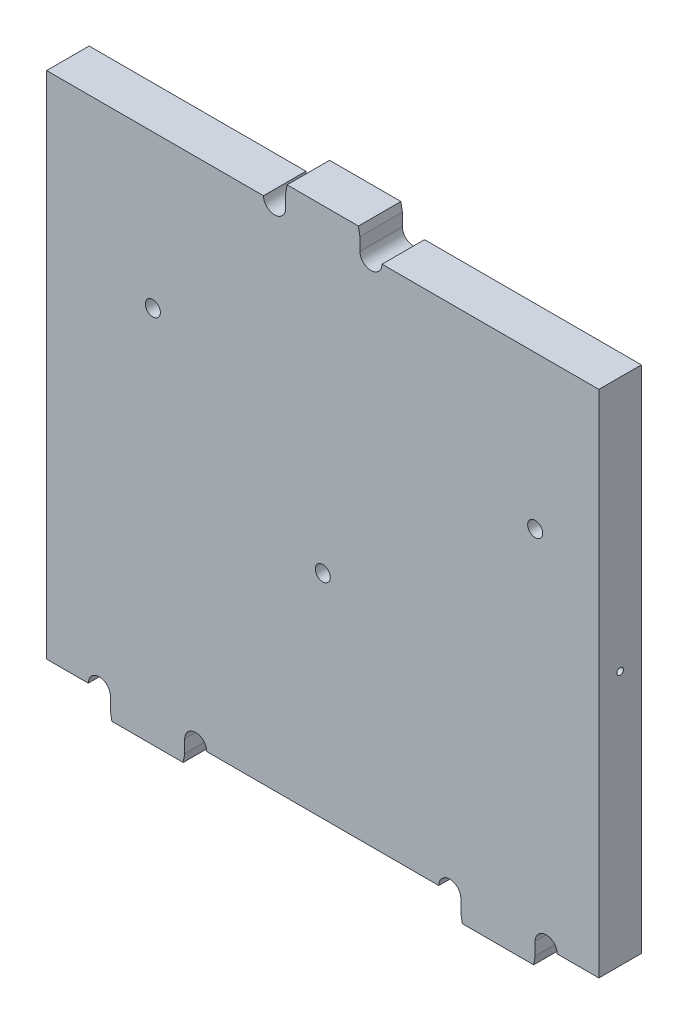
SolidWorks part; units mm, degrees
material "Delrin 2700 NC010, Low Viscosity Acetal Copolymer (SS)"
ref_plane "Front Plane" through (0, 0, 0) normal (0, 0, 1) x (1, 0, 0)
ref_plane "Top Plane" through (0, 0, 0) normal (0, 1, 0) x (1, 0, 0)
ref_plane "Right Plane" through (0, 0, 0) normal (1, 0, 0) x (0, 0, -1)
sketch "Sketch1" plane through (0, 0, 0) normal (0, 0, 1) x (1, 0, 0)
  line L1 (-82.55, -76.2) -> (82.55, -76.2)
  line L2 (-82.55, -76.2) -> (-82.55, 76.2)
  line L3 (-82.55, 76.2) -> (82.55, 76.2)
  line L4 (82.55, -76.2) -> (82.55, 76.2)
  line L5 (-82.55, -76.2) -> (82.55, 76.2) construction
  line L6 (-82.55, 76.2) -> (82.55, -76.2) construction
  point P0 (0, 0)
  dimension "D1" = 165.1
  dimension "D2" = 152.4
extrude "Boss-Extrude1" add sketch "Sketch1" along normal blind 12.7
sketch "Sketch2" plane through (0, 0, 12.7) normal (0, 0, 1) x (1, 0, 0)
  line L0 (82.55, 76.2) -> (-82.55, 76.2) construction
  line L1 (-11.1125, 76.2) -> (11.1125, 76.2)
  line L2 (-11.1125, 76.2) -> (-11.1125, 80.01)
  line L3 (-10.6646, 82.55) -> (10.6646, 82.55)
  line L4 (11.1125, 76.2) -> (11.1125, 80.01)
  line L5 (10.6646, 82.55) -> (11.1125, 80.01)
  line L6 (-10.6646, 82.55) -> (-11.1125, 80.01)
  line L7 (82.55, -76.2) -> (82.55, 76.2) construction
  point P6 (0, 82.55)
  dimension "D3" = 170
  dimension "D4" = 170
  dimension "D5" = 3.81
  dimension "D1" = 71.4375
  dimension "D2" = 6.35
extrude "Boss-Extrude2" add sketch "Sketch2" against normal up to surface (12.7 mm away) up to face at (0, 0, 0)
sketch "Sketch4" plane through (0, 0, 12.7) normal (0, 0, 1) x (1, 0, 0)
  line L0 (-11.1125, 76.2) -> (-82.55, 76.2) construction
  line L1 (-11.1125, 80.01) -> (-11.1125, 76.2) construction
  line L2 (-82.55, 76.2) -> (82.55, 76.2) construction
  line L3 (0, 82.55) -> (0, 0) construction
  line L4 (10.6646, 82.55) -> (-10.6646, 82.55) construction
  line L5 (-17.7165, 76.2) -> (-11.1125, 76.2)
  line L6 (11.1125, 76.2) -> (17.7165, 76.2)
  arc A0 (-17.7165, 76.2) -> (-11.1125, 76.2) centre (-14.4145, 76.2) ccw
  arc A1 (17.7165, 76.2) -> (11.1125, 76.2) centre (14.4145, 76.2) cw
  dimension "D1" = 6.604
  dimension "D2" = 3.302
extrude "Cut-Extrude1" cut sketch "Sketch4" against normal up to next contours A1 L6 | A0 L5
sketch "Sketch5" plane through (0, 0, 12.7) normal (0, 0, 1) x (1, 0, 0)
  line L0 (-82.55, -76.2) -> (82.55, -76.2) construction
  line L1 (63.5, -76.2) -> (41.275, -76.2)
  line L2 (63.5, -76.2) -> (63.5, -80.01)
  line L3 (63.0521, -82.55) -> (41.7229, -82.55)
  line L4 (41.275, -76.2) -> (41.275, -80.01)
  line L5 (82.55, -76.2) -> (82.55, 76.2) construction
  line L6 (41.275, -80.01) -> (41.7229, -82.55)
  line L7 (63.5, -80.01) -> (63.0521, -82.55)
  dimension "D1" = 22.225
  dimension "D2" = 6.35
  dimension "D3" = 19.05
  dimension "D4" = 170
  dimension "D5" = 170
  dimension "D6" = 3.81
extrude "Boss-Extrude3" add sketch "Sketch5" against normal up to surface (12.7 mm away) up to face at (0, 51.943, 0)
sketch "Sketch6" plane through (0, 0, 12.7) normal (0, 0, 1) x (1, 0, 0)
  line L0 (-82.55, -76.2) -> (41.275, -76.2) construction
  line L1 (82.55, -76.2) -> (0, -76.2) construction
  line L2 (34.671, -76.2) -> (41.275, -76.2)
  line L3 (52.3875, -82.55) -> (52.3875, 76.2) construction
  line L4 (41.7229, -82.55) -> (63.0521, -82.55) construction
  line L5 (82.55, 76.2) -> (17.7165, 76.2) construction
  line L6 (63.5, -76.2) -> (70.104, -76.2)
  arc A0 (41.275, -76.2) -> (34.671, -76.2) centre (37.973, -76.2) ccw
  arc A1 (63.5, -76.2) -> (70.104, -76.2) centre (66.802, -76.2) cw
  dimension "D1" = 6.604
  dimension "D2" = 3.302
extrude "Cut-Extrude2" cut sketch "Sketch6" against normal up to surface (12.7 mm away) up to face at (17.4625, 8.0998, 0)
mirror "Mirror1" about plane through (0, 0, 0) normal (1, 0, 0) of "Boss-Extrude3", "Cut-Extrude2"
sketch "Sketch7" plane through (0, 0, 12.7) normal (0, 0, 1) x (1, 0, 0)
  line L0 (-34.671, -76.2) -> (34.671, -76.2) construction
  line L1 (-82.55, 76.2) -> (-82.55, -76.2) construction
  line L2 (82.55, -76.2) -> (82.55, 76.2) construction
  circle A0 centre (-47.625, -41.275) radius 11.1125 construction
  circle A1 centre (47.625, -41.275) radius 11.1125 construction
  point P6 (0, 0)
  point P11 (0, 0)
  dimension "D4" = 22.225
  dimension "D5" = 22.225
  dimension "D1" = 34.925
  dimension "D2" = 34.925
  dimension "D3" = 34.925
hole_wizard "#8 Clearance Hole1" positions "Sketch16" profile "Sketch17" hole size "#8" standard "ANSI Inch" end condition through all
sketch "Sketch16" plane through (0, 0, 12.7) normal (0, 0, 1) x (1, 0, 0)
  line L0 (-82.55, 76.2) -> (-82.55, -76.2) construction
  circle A0 centre (-47.625, -41.275) radius 55.5625 construction
  circle A1 centre (47.625, -41.275) radius 55.5625 construction
  circle A2 centre (0, -12.6559) radius 66.675 construction
  circle A3 centre (-50.8, 30.5287) radius 114.3 construction
  point P0 (0, -12.6559)
  point P3 (63.5, 30.5287)
  point P6 (-50.8, 30.5287)
  point P39 (0, 0)
  dimension "D1" = 111.125
  dimension "D2" = 111.125
  dimension "D3" = 133.35
  dimension "D5" = 228.6
  dimension "D4" = 31.75
sketch "Sketch17" plane through (0, -12.6559, 12.7) normal (1, 0, 0) x (0, -1, 0)
  line L0 (0, 0) -> (0, 12.7)
  line L1 (0, 12.7) -> (2.2479, 12.7)
  line L2 (2.2479, 12.7) -> (2.2479, 0)
  line L5 (2.2479, 0) -> (0, 0)
  line L11 (0, -6.35) -> (0, 107.95) construction
  dimension "Thru Hole Dia." = 4.4958
  dimension "Thru Hole Depth" = 12.7
sketch "Sketch20" plane through (82.55, 0, 0) normal (1, 0, 0) x (0, 0, -1)
  line L1 (-12.7, -76.2) -> (0, -76.2) construction
  circle A0 centre (-6.35, 0) radius 0.9919
  point P0 (-6.35, 0)
  point P2 (-6.35, 0)
  point P7 (-6.35, -76.2)
  dimension "D2" = 1.9837
  dimension "D1" = 76.2
extrude "Cut-Extrude9" cut sketch "Sketch20" against normal blind 25.4
mirror "Mirror3" about plane through (0, 0, 0) normal (1, 0, 0) of "Cut-Extrude9"
sketch "Sketch21" plane through (0, 0, 0) normal (0, 0, -1) x (-1, 0, 0)
  circle A0 centre (0, -12.6559) radius 3.175
  circle A1 centre (-63.5, 30.5287) radius 4.7625
  circle A2 centre (50.8, 30.5287) radius 4.7625
  dimension "D1" = 6.35
  dimension "D2" = 9.525
  dimension "D3" = 9.525
extrude "Cut-Extrude10" cut sketch "Sketch21" against normal blind 6.35
equation "\"D4@Sketch2\"=\"D3@Sketch2\""
equation "\"D2@Sketch4\"=\"D1@Sketch4\"/2"
equation "\"D2@Sketch6\"=\"D1@Sketch6\"/2"
equation "\"D3@Sketch7\"=\"D2@Sketch7\""
equation "\"D5@Sketch7\"=\"D4@Sketch7\""
equation "\"D2@Sketch16\"=\"D1@Sketch16\""
equation "\"D3@Sketch21\"=\"D2@Sketch21\""
